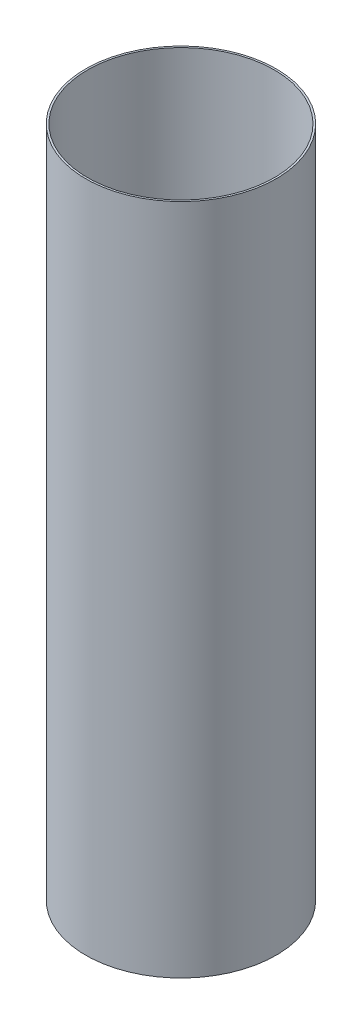
SolidWorks part; units mm, degrees
material "PBT Общее назначение"
ref_plane "Спереди" through (0, 0, 0) normal (0, 0, 1) x (1, 0, 0)
ref_plane "Сверху" through (0, 0, 0) normal (0, 1, 0) x (1, 0, 0)
ref_plane "Справа" through (0, 0, 0) normal (1, 0, 0) x (0, 0, -1)
sketch "Эскиз1" plane through (0, 0, 0) normal (0, 1, 0) x (1, 0, 0)
  circle A0 centre (0, 0) radius 51
  circle A1 centre (0, 0) radius 50
  dimension "D1" = 100
  dimension "D2" = 102
extrude "Бобышка-Вытянуть1" add sketch "Эскиз1" along normal blind 360
